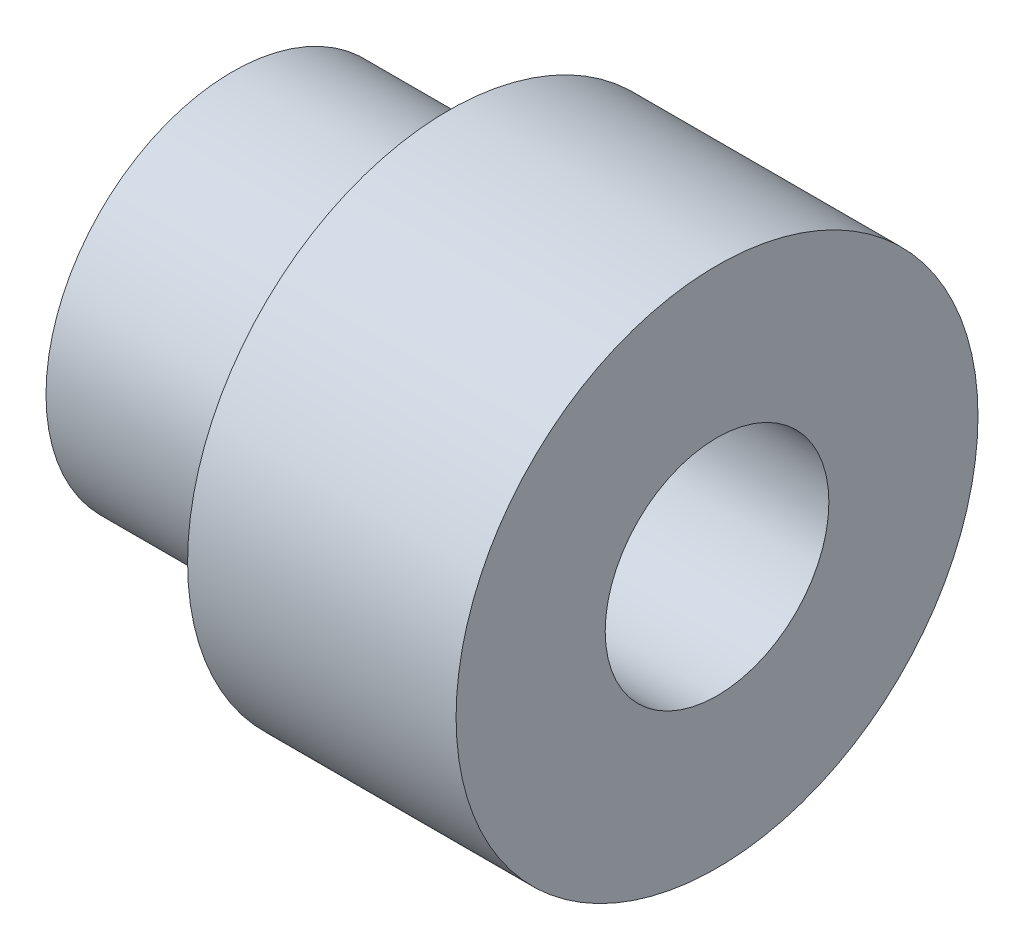
SolidWorks part; units mm, degrees
material "AISI 316 Stainless Steel Sheet (SS)"
ref_plane "Front Plane" through (0, 0, 0) normal (0, 0, 1) x (1, 0, 0)
ref_plane "Top Plane" through (0, 0, 0) normal (0, 1, 0) x (1, 0, 0)
ref_plane "Right Plane" through (0, 0, 0) normal (1, 0, 0) x (0, 0, -1)
sketch "Sketch1" plane through (0, 0, 0) normal (0, 0, 1) x (1, 0, 0)
  line L0 (0, 0) -> (0, 5)
  line L1 (0, 5) -> (5.7977, 5)
  line L2 (5.7977, 5) -> (5.7977, 7)
  line L3 (5.7977, 7) -> (13, 7)
  line L4 (13, 7) -> (13, 0)
  line L5 (13, 0) -> (0, 0)
  line L6 (0, 0) -> (14.2253, 0) construction
  dimension "D1" = 13
  dimension "D2" = 5
  dimension "D3" = 7
revolve "Revolve1" add sketch "Sketch1" angle 360 about L6
sketch "Sketch3" plane through (0, 0, 0) normal (1, 0, 0) x (0, 0, -1)
  circle A0 centre (0, 0) radius 3
  dimension "D1" = 6
extrude "Cut-Extrude1" cut sketch "Sketch3" along normal through all
